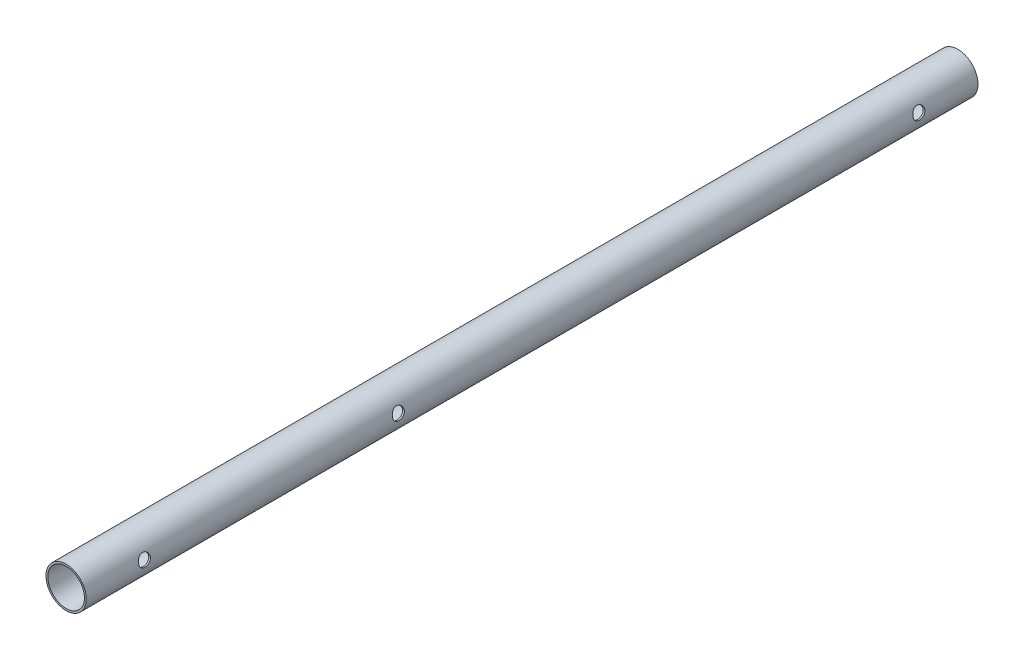
SolidWorks part; units mm, degrees
ref_plane "Front Plane" through (0, 0, 0) normal (0, 0, 1) x (1, 0, 0)
ref_plane "Top Plane" through (0, 0, 0) normal (0, 1, 0) x (1, 0, 0)
ref_plane "Right Plane" through (0, 0, 0) normal (1, 0, 0) x (0, 0, -1)
sketch "Sketch1" plane through (0, 0, 0) normal (0, 0, 1) x (1, 0, 0)
  circle A0 centre (0, 0) radius 10
  circle A1 centre (0, 0) radius 11
  dimension "D1" = 20
  dimension "D2" = 22
extrude "Boss-Extrude1" add sketch "Sketch1" against normal blind 486.5
sketch "Sketch2" plane through (0, 0, 0) normal (0, 0, 1) x (1, 0, 0)
  point P0 (10.2692, 2.145)
ref_plane "Plane1" through (10.7676, 2.2492, 0) normal (0.9789, 0.2045, 0) x (0, 0, -1)
sketch "Sketch3" plane through (10.7676, 2.2492, 0) normal (0.9789, 0.2045, 0) x (0, 0, -1)
  line L0 (0, 11) -> (0, -11) construction
  circle A0 centre (32, 0) radius 3.25
  circle A1 centre (170.5, 0) radius 3.25
  circle A2 centre (454.5, 0) radius 3.25
  dimension "D1" = 6.5
  dimension "D2" = 32
  dimension "D3" = 2
  dimension "D4" = 2
extrude "Cut-Extrude1" cut sketch "Sketch3" against normal through all
